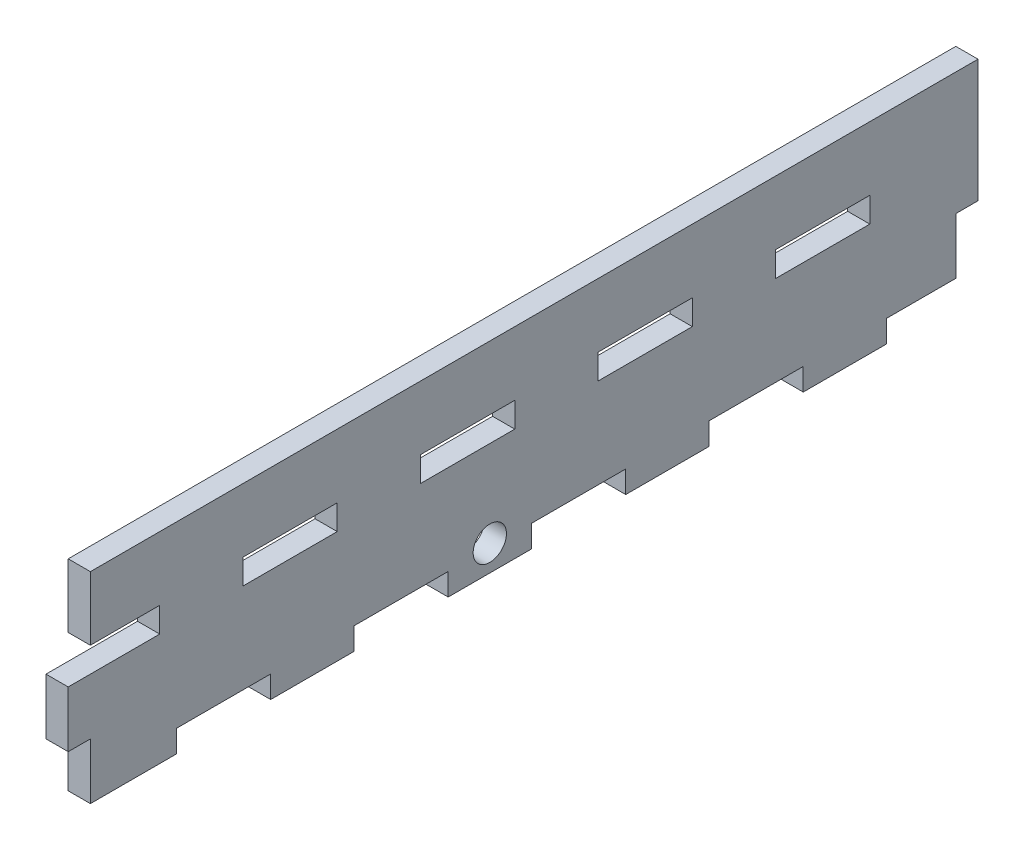
SolidWorks part; units mm, degrees
ref_plane "Plan de face" through (0, 0, 0) normal (0, 0, 1) x (1, 0, 0)
ref_plane "Plan de dessus" through (0, 0, 0) normal (0, 1, 0) x (1, 0, 0)
ref_plane "Plan de droite" through (0, 0, 0) normal (1, 0, 0) x (0, 0, -1)
sketch "Esquisse1" plane through (0, 0, 0) normal (1, 0, 0) x (0, 0, -1)
  line L5 (-41.0892, -6.055) -> (40.9108, -6.055)
  line L6 (-41.0892, -6.055) -> (-41.0892, 6.055)
  line L7 (-41.0892, 6.055) -> (40.9108, 6.055)
  line L8 (40.9108, -6.055) -> (40.9108, 6.055)
extrude "Boss.-Extru.1" add sketch "Esquisse1" along normal blind 2
sketch "Esquisse2" plane through (0, 0, 0) normal (1, 0, 0) x (0, 0, -1)
  line L0 (-33.0892, 4.055) -> (-33.0892, 6.055) construction
  line L1 (-41.3392, 6.305) -> (-32.8392, 6.305)
  line L2 (-41.3392, 6.305) -> (-41.3392, 4.055)
  line L3 (-41.3392, 4.055) -> (-32.8392, 4.055)
  line L4 (-32.8392, 6.305) -> (-32.8392, 4.055)
  line L5 (-41.0892, 6.305) -> (-41.0892, 6.055) construction
  line L6 (-41.0892, 6.055) -> (-41.3392, 6.055) construction
  line L8 (-33.0892, 5.18) -> (-32.8392, 5.18) construction
  line L9 (-41.0892, 4.055) -> (-33.0892, 4.055) construction
  line L11 (-25.3392, 6.305) -> (-16.8392, 6.305)
  line L12 (-16.8392, 6.305) -> (-16.8392, 4.055)
  line L13 (-25.3392, 4.055) -> (-16.8392, 4.055)
  line L14 (-25.3392, 6.305) -> (-25.3392, 4.055)
  line L15 (-9.3392, 6.305) -> (-0.8392, 6.305)
  line L16 (-0.8392, 6.305) -> (-0.8392, 4.055)
  line L17 (-9.3392, 4.055) -> (-0.8392, 4.055)
  line L18 (-9.3392, 6.305) -> (-9.3392, 4.055)
  line L19 (6.6608, 6.305) -> (15.1608, 6.305)
  line L20 (15.1608, 6.305) -> (15.1608, 4.055)
  line L21 (6.6608, 4.055) -> (15.1608, 4.055)
  line L22 (6.6608, 6.305) -> (6.6608, 4.055)
  line L23 (22.6608, 6.305) -> (31.1608, 6.305)
  line L24 (31.1608, 6.305) -> (31.1608, 4.055)
  line L25 (22.6608, 4.055) -> (31.1608, 4.055)
  line L26 (22.6608, 6.305) -> (22.6608, 4.055)
  line L27 (-32.8392, 4.055) -> (-25.3392, 4.055) construction
  line L29 (-25.3392, 5.18) -> (-25.0892, 5.18) construction
  line L30 (-25.0892, 6.055) -> (-25.0892, 4.055) construction
  dimension "D3" = 0.25
  dimension "D2" = 5
extrude "Enlèv. mat.-Extru.1" cut sketch "Esquisse2" along normal through all
sketch "Esquisse3" plane through (0, 0, 0) normal (1, 0, 0) x (0, 0, -1)
  line L0 (-41.0892, -6.055) -> (40.9108, -6.055) construction
  line L1 (-31.3392, -6.055) -> (-22.8392, -6.055)
  line L2 (-31.3392, -6.055) -> (-31.3392, -4.055)
  line L3 (-31.3392, -4.055) -> (-22.8392, -4.055)
  line L4 (-22.8392, -6.055) -> (-22.8392, -4.055)
  line L7 (-25.3392, 4.055) -> (-16.8392, 4.055) construction
  line L8 (-32.8392, 4.055) -> (-32.8392, 6.055) construction
  line L9 (-31.3392, -5.055) -> (-31.0892, -5.055) construction
  line L10 (-31.0892, -6.055) -> (-31.0892, -4.055) construction
  line L11 (-32.8392, 5.2908) -> (-33.0892, 5.2908) construction
  line L12 (-32.8392, 4.055) -> (-32.8392, 6.055) construction
  line L13 (-33.0892, 4.055) -> (-33.0892, 6.055) construction
  line L14 (-15.3392, -6.055) -> (-6.8392, -6.055)
  line L15 (-15.3392, -6.055) -> (-15.3392, -4.055)
  line L16 (-15.3392, -4.055) -> (-6.8392, -4.055)
  line L17 (-6.8392, -6.055) -> (-6.8392, -4.055)
  line L18 (-15.3392, -5.055) -> (-15.0892, -5.055) construction
  line L19 (0.6608, -6.055) -> (9.1608, -6.055)
  line L20 (0.6608, -6.055) -> (0.6608, -4.055)
  line L21 (0.6608, -4.055) -> (9.1608, -4.055)
  line L22 (9.1608, -6.055) -> (9.1608, -4.055)
  line L23 (0.6608, -5.055) -> (0.9108, -5.055) construction
  line L24 (16.6608, -6.055) -> (25.1608, -6.055)
  line L25 (16.6608, -6.055) -> (16.6608, -4.055)
  line L26 (16.6608, -4.055) -> (25.1608, -4.055)
  line L27 (25.1608, -6.055) -> (25.1608, -4.055)
  line L28 (16.6608, -5.055) -> (16.9108, -5.055) construction
  line L29 (32.6608, -6.055) -> (41.1608, -6.055)
  line L30 (32.6608, -6.055) -> (32.6608, -4.055)
  line L31 (32.6608, -4.055) -> (41.1608, -4.055)
  line L32 (41.1608, -6.055) -> (41.1608, -4.055)
  line L33 (32.6608, -5.055) -> (32.9108, -5.055) construction
  line L40 (48.6608, -6.055) -> (57.1608, -6.055) [skipped]
  line L41 (48.6608, -6.055) -> (48.6608, -4.055) [skipped]
  line L42 (48.6608, -4.055) -> (57.1608, -4.055) [skipped]
  line L43 (48.6608, -5.055) -> (48.9108, -5.055) construction
  line L44 (57.1608, -6.055) -> (57.1608, -4.055) [skipped]
  line L45 (40.9108, -6.055) -> (40.9108, -4.055) construction
  dimension "D2" = 0.25
  dimension "D1" = 6
extrude "Enlèv. mat.-Extru.2" cut sketch "Esquisse3" along normal through all
sketch "Esquisse4" plane through (2, 0, 0) normal (1, 0, 0) x (0, 0, -1)
  line L0 (-39.0892, -1) -> (-39.0892, 4.055) construction
  line L1 (-41.0892, -6.055) -> (-39.0892, -6.055)
  line L2 (-41.0892, -6.055) -> (-41.0892, -1)
  line L3 (-41.0892, -1) -> (-39.0892, -1)
  line L4 (-39.0892, -6.055) -> (-39.0892, -1)
  line L5 (-41.0892, 4.055) -> (-33.0892, 4.055) construction
  line L6 (-41.0892, 6.055) -> (-41.0892, 4.055) construction
  line L8 (40.9108, -4.055) -> (38.9108, -4.055)
  line L9 (40.9108, -4.055) -> (40.9108, 1)
  line L10 (40.9108, 1) -> (38.9108, 1)
  line L11 (38.9108, -4.055) -> (38.9108, 1)
extrude "Enlèv. mat.-Extru.3" cut sketch "Esquisse4" against normal through all
sketch "Esquisse5" plane through (0, 0, 0) normal (-1, 0, 0) x (0, 0, 1)
  line L0 (39.0892, -6.055) -> (39.0892, -1) construction
  line L1 (-40.9108, 6.055) -> (39.0892, 6.055)
  line L2 (-40.9108, 6.055) -> (-40.9108, 12.055)
  line L3 (-40.9108, 12.055) -> (39.0892, 12.055)
  line L4 (39.0892, 6.055) -> (39.0892, 12.055)
  dimension "D1" = 6
extrude "Boss.-Extru.2" add sketch "Esquisse5" against normal blind 2
sketch "Esquisse6" plane through (2, 0, 0) normal (1, 0, 0) x (0, 0, -1)
  line L0 (31.1608, 4.055) -> (31.1608, 6.055) construction
  line L1 (-32.8392, 6.305) -> (-39.0892, 6.305)
  line L2 (-32.8392, 6.305) -> (-32.8392, 6.055)
  line L3 (-32.8392, 6.055) -> (-39.0892, 6.055)
  line L4 (-39.0892, 6.305) -> (-39.0892, 6.055)
  line L5 (-25.3392, 6.055) -> (-16.8392, 6.055)
  line L6 (-25.3392, 6.055) -> (-25.3392, 6.305)
  line L7 (-25.3392, 6.305) -> (-16.8392, 6.305)
  line L8 (-16.8392, 6.055) -> (-16.8392, 6.305)
  line L9 (-9.3392, 6.055) -> (-0.8392, 6.055)
  line L10 (-9.3392, 6.055) -> (-9.3392, 6.305)
  line L11 (-9.3392, 6.305) -> (-0.8392, 6.305)
  line L12 (-0.8392, 6.055) -> (-0.8392, 6.305)
  line L13 (6.6608, 6.055) -> (15.1608, 6.055)
  line L14 (6.6608, 6.055) -> (6.6608, 6.305)
  line L15 (6.6608, 6.305) -> (15.1608, 6.305)
  line L16 (15.1608, 6.055) -> (15.1608, 6.305)
  line L17 (22.6608, 6.055) -> (31.1608, 6.055)
  line L18 (22.6608, 6.055) -> (22.6608, 6.305)
  line L19 (22.6608, 6.305) -> (31.1608, 6.305)
  line L20 (31.1608, 6.055) -> (31.1608, 6.305)
  line L21 (31.1608, 6.055) -> (22.6608, 6.055) construction
  line L22 (15.1608, 4.055) -> (15.1608, 6.055) construction
  line L23 (15.1608, 6.055) -> (6.6608, 6.055) construction
  line L24 (-16.8392, 6.055) -> (-25.3392, 6.055) construction
  dimension "D1" = 0.25
extrude "Enlèv. mat.-Extru.4" cut sketch "Esquisse6" against normal through all
sketch "Sketch1" plane through (2, 0, 0) normal (1, 0, 0) x (0, 0, -1)
  circle A0 centre (-3.0892, -3.725) radius 1.5
  dimension "D1" = 3
extrude "Cut-Extrude1" cut sketch "Sketch1" against normal through all
